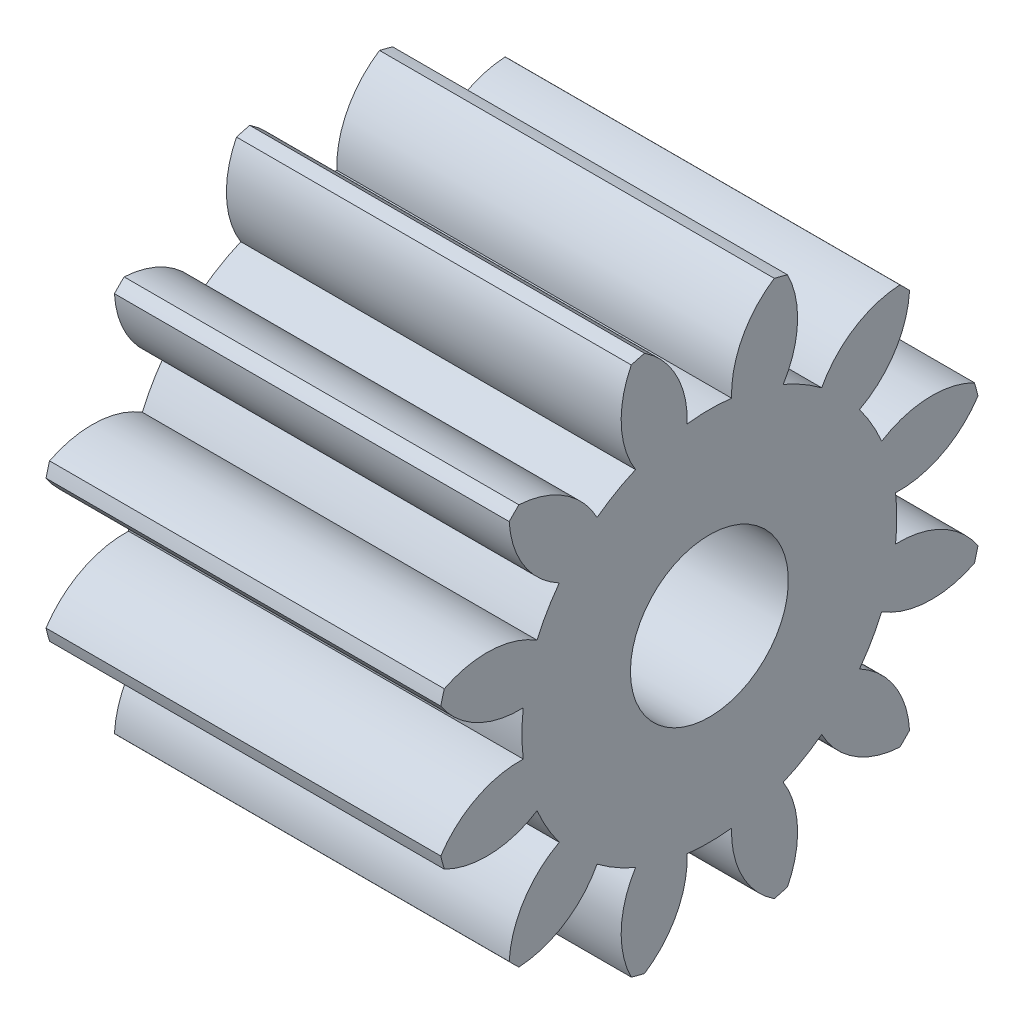
SolidWorks part; units mm, degrees
ref_plane "Plane1" through (0, 0, 0) normal (0, 0, 1) x (1, 0, 0)
ref_plane "Plane2" through (0, 0, 0) normal (0, 1, 0) x (1, 0, 0)
ref_plane "Plane3" through (0, 0, 0) normal (1, 0, 0) x (0, 0, -1)
sketch "HoldingSke" plane through (0, 0, 0) normal (0, 1, 0) x (1, 0, 0)
  line L0 (0, 0) -> (0.9781, -0.2079)
  line L1 (-15, 0) -> (100, 0) construction
  line L2 (0, 0) -> (-2.1039, 2.3779)
  line L3 (0, 0) -> (-11.863, 4.5341)
  line L4 (0, 0) -> (8.4473, 1.7955)
  line L5 (0, 0) -> (-46.8476, -17.4728)
  line L6 (0, 0) -> (-8.2896, -5.593)
  line L7 (-2.1039, 2.3779) -> (8.6586, 51.2059)
  line L8 (-76.2, 54.61) -> (-75.5, 54.61)
  line L9 (-71.009, 38.7566) -> (-53.1078, 45.2721)
  line L10 (-76.2, 71.12) -> (104.1128, 71.12)
  line L11 (0, 0) -> (-10, 0)
  line L12 (-76.2, 101.6) -> (-76.162, 101.6)
  line L13 (24.9733, 27.94) -> (52.9518, 28.4284)
  line L14 (24.9733, 27.94) -> (24.9743, 27.94)
  line L15 (24.9733, 27.94) -> (100.4006, 29.5858)
  line L16 (-63.627, -1) -> (-12.827, -1)
  circle A0 centre (0, 0) radius 2
  circle A1 centre (0, 0) radius 4.749
  circle A2 centre (0, 0) radius 37.5
  circle A3 centre (0, 0) radius 2
  dimension "MHD" = 9.498
  dimension "Hub_dia" = 75
  dimension "Bore" = 4
  dimension "MBD" = 4
  dimension "Num_teeth" = 12
  dimension "Pitch" = 1
  dimension "Overall_len" = 50
  dimension "Show_teeth" = 12
  dimension "Thickness" = 10
  dimension "OAL" = 50.0001
  dimension "T_dim" = 0.7
  dimension "Ap" = 20
  dimension "H" = 19.05
  dimension "Pitch_radius" = 180.3128
  dimension "Width" = 10
  dimension "Backlash" = 0.038
  dimension "Addendum_fac" = 1
  dimension "Dedendum_fac" = 1.25
  dimension "Clearance_fac" = 0.25
  dimension "Dedendum_add" = 0.001
  dimension "Module" = 1
sketch "BasProSke" plane through (0, 0, 0) normal (0, 1, 0) x (1, 0, 0)
  line L0 (-10, 0) -> (60, 0) construction
  line L1 (0, 0) -> (0, 7)
  line L2 (0, 0) -> (10, 0)
  line L3 (10, 0) -> (10, 7)
  line L4 (10, 7) -> (0, 7)
  dimension "Thickness" = 10
  dimension "Diameter" = 14
revolve "Base-Revolve" add sketch "BasProSke" angle 360 about L0
sketch "TooCutSke" plane through (0, 0, 0) normal (1, 0, 0) x (0, 0, -1)
  line L1 (0, 0) -> (0, 107) construction
  line L2 (0, 0) -> (-0.8496, 5.9395) construction
  line L3 (0, 0) -> (-3.0836, 11.5081) construction
  line L4 (-0.8496, 5.9395) -> (-1.5418, 5.7541) construction
  arc A0 (0.5622, 4.7156) -> (-0.5622, 4.7156) centre (0, 0) ccw
  arc A1 (1.6729, 6.8233) -> (-1.6729, 6.8233) centre (0, 0) ccw
  circle A2 centre (0, 0) radius 6 construction
  circle A3 centre (0, 0) radius 5.6382 construction
  arc A4 (-0.5622, 4.7156) -> (-1.6729, 6.8233) centre (-2.9608, 4.7982) ccw
  arc A5 (1.6729, 6.8233) -> (0.5622, 4.7156) centre (2.9608, 4.7982) ccw
  dimension "Root_dia" = 9.498
  dimension "Overcut_dia" = 14.0508
  dimension "Pitch_dia" = 12
  dimension "Base_dia" = 11.2763
  dimension "Flank_rad" = 2.4
  dimension "Half_ang" = 15
  dimension "Half_CT" = 0.7167
extrude "ToothCut" cut sketch "TooCutSke" along normal through all
fillet "Breaks" [suppressed] radius 0.02
fillet "RootFillets" [suppressed] radius 0.251
pattern_circular "TeethCuts" count 12 every 30 about axis through (-10, 0, 0) along (1, 0, 0) of "ToothCut", "RootFillets", "Breaks"
sketch "HubNeaOneSke" plane through (0, 0, 0) normal (-1, 0, 0) x (0, 0, 1)
  circle A0 centre (0, 0) radius 4.749
  dimension "Diameter" = 9.498
extrude "HubNearOne" [suppressed] add sketch "HubNeaOneSke" along normal blind 40.0001
sketch "HubNeaBotSke" plane through (0, 0, 0) normal (-1, 0, 0) x (0, 0, 1)
  circle A0 centre (0, 0) radius 4.749
  dimension "Diameter" = 9.498
extrude "HubNearBoth" [suppressed] add sketch "HubNeaBotSke" along normal blind 20
ref_plane "FarPln" through (10, 0, 0) normal (1, 0, 0) x (0, 0, -1)
sketch "HubFarSke" plane through (10, 0, 0) normal (1, 0, 0) x (0, 0, -1)
  circle A0 centre (0, 0) radius 4.749
  dimension "Diameter" = 9.498
extrude "HubFar" [suppressed] add sketch "HubFarSke" along normal blind 20
sketch "BorSke" plane through (0, 0, 0) normal (1, 0, 0) x (0, 0, -1)
  circle A0 centre (0, 0) radius 2
  dimension "Diameter" = 4
extrude "Bore" cut sketch "BorSke" along normal mid plane 100.0001
sketch "KeySke" plane through (0, 0, 0) normal (1, 0, 0) x (0, 0, -1)
  line L0 (-0.8, 0) -> (-0.8, 2.7)
  line L1 (-0.8, 2.7) -> (0.8, 2.7)
  line L2 (0.8, 2.7) -> (0.8, 0)
  line L3 (0, 0) -> (0, 34) construction
  line L4 (-0.8, 0) -> (0.8, 0)
  dimension "Offset" = 2.7
  dimension "Width" = 1.6
extrude "Keyway" [suppressed] cut sketch "KeySke" along normal mid plane 100.0001
pattern_circular "Keyway2" [suppressed] count 2 every 90 about axis through (-10, 0, 0) along (1, 0, 0)
sketch "草图2" plane through (0, 0, 0) normal (1, 0, 0) x (0, 0, -1)
  circle A0 centre (0, 0) radius 6
  dimension "D1" = 12
chamfer "倒角1" distance 2 angle 45 1 edges at (0, 0, -2)
equation "' \"Module@HoldingSke\" = 6.35"
equation "' \"Num_teeth@HoldingSke\" = 12"
equation "' \"Ap@HoldingSke\" =  20"
equation "' \"Ap@HoldingSke\" = 20"
equation "' \"Width@HoldingSke\" = 0.5 * 25.4"
equation "' \"Hub_dia@HoldingSke\"= 1 * 25.4"
equation "' \"Hub_dia@HoldingSke\" = 1 * 25.4"
equation "' \"Overall_len@HoldingSke\" = 1.0 * 25.4"
equation "' \"Bore@HoldingSke\" = 0.75 * 25.4"
equation "' \"T_dim@HoldingSke\" = 0.1 * 25.4"
equation "' \"Width@KeySke\" = 0.25 * 25.4"
equation "' \"Show_teeth@HoldingSke\" = 13"
equation "' \"Backlash@HoldingSke\" = 0.009 * 25.4"
equation "' \"Addendum_fac@HoldingSke\" = 1.0"
equation "' \"Dedendum_fac@HoldingSke\" = 1.25"
equation "' \"Dedendum_add@HoldingSke\" = 0.00005 * 25.4"
equation "' \"Clearance_fac@HoldingSke\" = 0.25"
equation "\"Pitch@HoldingSke\" = 1 / \"Module@HoldingSke\""
equation "\"Overcut_dia@TooCutSke\" = (\"Num_teeth@HoldingSke\" + 2 * \"Addendum_fac@HoldingSke\") / \"Pitch@HoldingSke\" + 0.002 * 25.4"
equation "\"Pitch_dia@TooCutSke\" = \"Num_teeth@HoldingSke\" / \"Pitch@HoldingSke\""
equation "\"Base_dia@TooCutSke\" = \"Num_teeth@HoldingSke\" / \"Pitch@HoldingSke\" * cos((\"Ap@HoldingSke\"  * 3.14159265 / 180))"
equation "\"Root_dia@TooCutSke\" = (\"Num_teeth@HoldingSke\" + 2) / \"Pitch@HoldingSke\" - 2 * (\"Addendum_fac@HoldingSke\" + \"Dedendum_fac@HoldingSke\") / \"Pitch@HoldingSke\" - \"Dedendum_add@HoldingSke\" * 2"
equation "\"Half_ang@TooCutSke\" = 180 / \"Num_teeth@HoldingSke\""
equation "\"Half_CT@TooCutSke\" = \"Num_teeth@HoldingSke\" / \"Pitch@HoldingSke\" * sin((3.14159265 / 2 / \"Num_teeth@HoldingSke\")) / 2 - 7 * \"Backlash@HoldingSke\" / 4"
equation "\"Flank_rad@TooCutSke\" = \"Num_teeth@HoldingSke\" / \"Pitch@HoldingSke\" / 5"
equation "\"Radius@RootFillets\" = \"Clearance_fac@HoldingSke\" / \"Pitch@HoldingSke\" + \"Dedendum_add@HoldingSke\""
equation "\"Break_rad@Breaks\" = 0.02 / \"Pitch@HoldingSke\""
equation "\"Thickness@HoldingSke\" = \"Width@HoldingSke\""
equation "\"OAL@HoldingSke\" = \"Thickness@HoldingSke\""
equation "\"MHD@HoldingSke\" = (\"Num_teeth@HoldingSke\" + 2) / \"Pitch@HoldingSke\" - 2 * (\"Addendum_fac@HoldingSke\" + \"Dedendum_fac@HoldingSke\")  / \"Pitch@HoldingSke\" - \"Dedendum_add@HoldingSke\" * 2"
equation "\"MBD@HoldingSke\" = (\"Num_teeth@HoldingSke\" + 2) / \"Pitch@HoldingSke\" - 2 * (\"Addendum_fac@HoldingSke\" + \"Dedendum_fac@HoldingSke\")  / \"Pitch@HoldingSke\" - \"Dedendum_add@HoldingSke\" * 2 - 0.002 * 25.4"
equation "\"MHD@HoldingSke\" = ((sgn( \"MHD@HoldingSke\" - \"Hub_dia@HoldingSke\" )-1)*( \"MHD@HoldingSke\" - \"Hub_dia@HoldingSke\" ))/-2+ \"Hub_dia@HoldingSke\""
equation "\"MBD@HoldingSke\" = ((sgn( \"MBD@HoldingSke\" - \"Bore@HoldingSke\" )-1)*( \"MBD@HoldingSke\" - \"Bore@HoldingSke\" ))/-2+ \"Bore@HoldingSke\""
equation "\"OAL@HoldingSke\" = ((sgn( \"OAL@HoldingSke\" - \"Overall_len@HoldingSke\" )+1)*( \"OAL@HoldingSke\" - \"Overall_len@HoldingSke\" ))/2 + \"Overall_len@HoldingSke\" + 0.000002 * 25.4"
equation "\"Num_teeth@TeethCuts\" = int( \"Show_teeth@HoldingSke\" ) + 1"
equation "\"Num_teeth@TeethCuts\" = ((sgn( \"Num_teeth@TeethCuts\" - \"Num_teeth@HoldingSke\" )-1)*( \"Num_teeth@TeethCuts\" - \"Num_teeth@HoldingSke\" ))/-2+ \"Num_teeth@HoldingSke\""
equation "\"Num_teeth@TeethCuts\" = ((sgn( \"Num_teeth@TeethCuts\" - 2.0)+1)*( \"Num_teeth@TeethCuts\" - 2.0))/2 +2.0"
equation "\"Angle@TeethCuts\" = 360.0 / \"Num_teeth@HoldingSke\""
equation "\"Diameter@BasProSke\" = (\"Num_teeth@HoldingSke\" + 2 * \"Addendum_fac@HoldingSke\") / \"Pitch@HoldingSke\""
equation "\"Thickness@BasProSke\"  = \"Thickness@HoldingSke\""
equation "' \"Fillet_rad@BasProSke\" =  \"Thickness@HoldingSke\" * 0.05"
equation "' \"Fillet_rad@BasProSke\" = \"Thickness@HoldingSke\" * 0.05"
equation "\"MHD@HoldingSke\" = ((sgn( \"MHD@HoldingSke\" - \"Root_dia@TooCutSke\" )-1)*( \"MHD@HoldingSke\" - \"Root_dia@TooCutSke\" ))/-2+ \"Root_dia@TooCutSke\""
equation "\"Diameter@HubNeaOneSke\" = \"MHD@HoldingSke\""
equation "\"Length@HubNearOne\" = \"OAL@HoldingSke\" - \"Thickness@BasProSke\""
equation "\"Diameter@HubNeaBotSke\" = \"MHD@HoldingSke\""
equation "\"Length@HubNearBoth\" = ( \"OAL@HoldingSke\" - \"Thickness@BasProSke\" ) / 2.0"
equation "\"Thickness@FarPln\" = \"Thickness@BasProSke\""
equation "\"Diameter@HubFarSke\" = \"MHD@HoldingSke\""
equation "\"Length@HubFar\" = ( \"OAL@HoldingSke\" - \"Thickness@BasProSke\" ) / 2.0"
equation "\"Diameter@BorSke\" = \"MBD@HoldingSke\""
equation "\"D1@Bore\" = \"OAL@HoldingSke\" * 2.0"
equation "\"D1@Keyway\" = \"OAL@HoldingSke\" * 2.0"
equation "\"Offset@KeySke\" = \"T_dim@HoldingSke\" + \"MBD@HoldingSke\" / 2.0"
